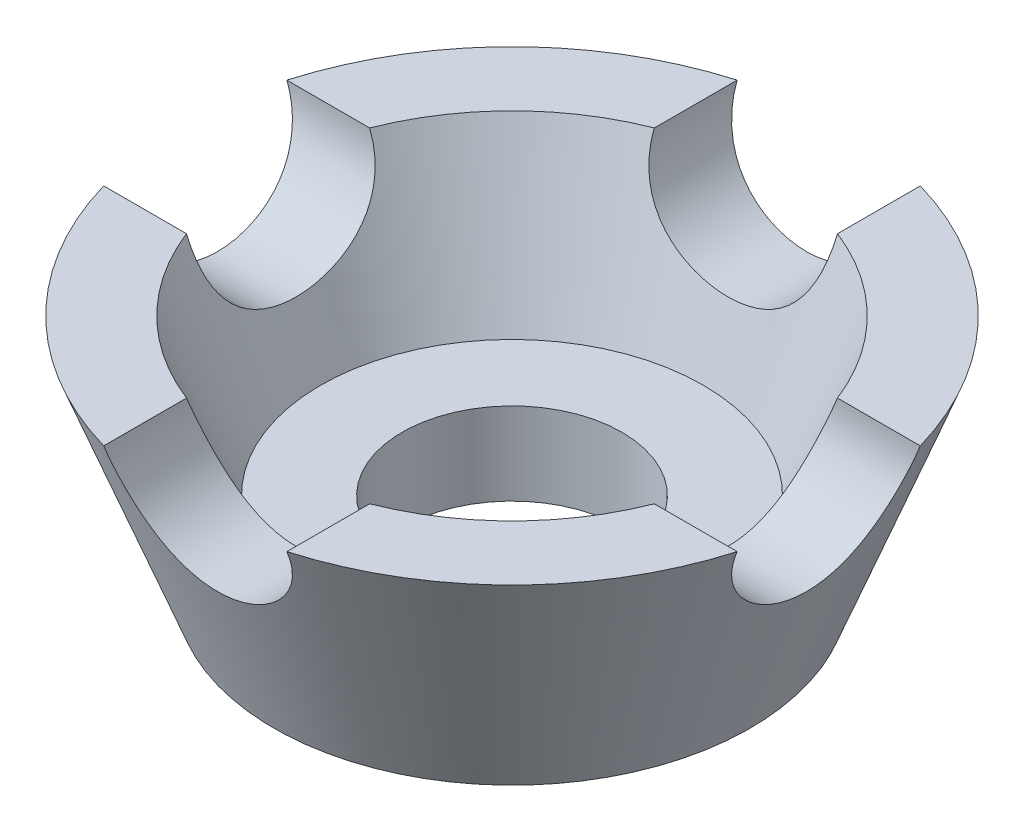
SolidWorks part; units mm, degrees
ref_plane "Front Plane" through (0, 0, 0) normal (0, 0, 1) x (1, 0, 0)
ref_plane "Top Plane" through (0, 0, 0) normal (0, 1, 0) x (1, 0, 0)
ref_plane "Right Plane" through (0, 0, 0) normal (1, 0, 0) x (0, 0, -1)
sketch "Sketch9" plane through (0, 0, 0) normal (0, 0, 1) x (1, 0, 0)
  line L0 (0, 0) -> (0, 26)
  line L1 (0, 0) -> (26, 0)
  line L2 (27.4287, 26) -> (36, 26)
  line L3 (36, 26) -> (26, 0)
  line L4 (0, 9) -> (20.8902, 9)
  line L5 (20.8902, 9) -> (27.4287, 26)
revolve "Revolve2" add sketch "Sketch9" angle 360 about L0
sketch "Sketch11" plane through (0, 0, 0) normal (0, 0, 1) x (1, 0, 0)
  line L0 (36, 26) -> (-36, 26) construction
  circle A0 centre (0, 26) radius 10
extrude "Cut-Extrude1" cut sketch "Sketch11" against normal through all both and the other way through all contours A0
sketch "Sketch12" plane through (0, 0, 0) normal (1, 0, 0) x (0, 0, -1)
  line L0 (34.5832, 26) -> (-34.5832, 26) construction
  circle A0 centre (0, 26) radius 10
extrude "Cut-Extrude2" cut sketch "Sketch12" against normal through all both and the other way through all
sketch "Sketch13" plane through (0, 9, 0) normal (0, 1, 0) x (1, 0, 0)
  circle A0 centre (0, 0) radius 12
extrude "Cut-Extrude3" cut sketch "Sketch13" against normal blind 26 contours A0
